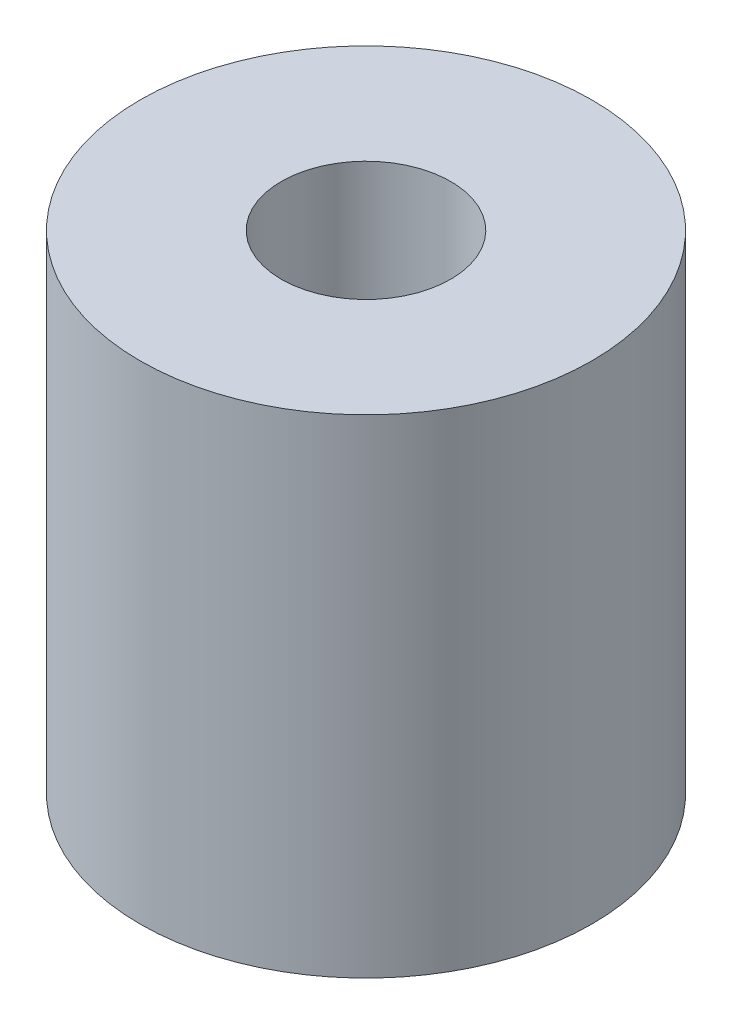
SolidWorks part; units mm, degrees
ref_plane "Front Plane" through (0, 0, 0) normal (0, 0, 1) x (1, 0, 0)
ref_plane "Top Plane" through (0, 0, 0) normal (0, 1, 0) x (1, 0, 0)
ref_plane "Right Plane" through (0, 0, 0) normal (1, 0, 0) x (0, 0, -1)
sketch "Sketch1" plane through (0, 0, 0) normal (0, 1, 0) x (1, 0, 0)
  circle A0 centre (0, 0) radius 4
  dimension "D1" = 8
extrude "Boss-Extrude1" add sketch "Sketch1" along normal blind 8.636
sketch "Sketch2" plane through (0, 8.636, 0) normal (0, 1, 0) x (1, 0, 0)
  circle A0 centre (0, 0) radius 1.5
  dimension "D1" = 3
extrude "Cut-Extrude1" cut sketch "Sketch2" against normal blind 7.62
